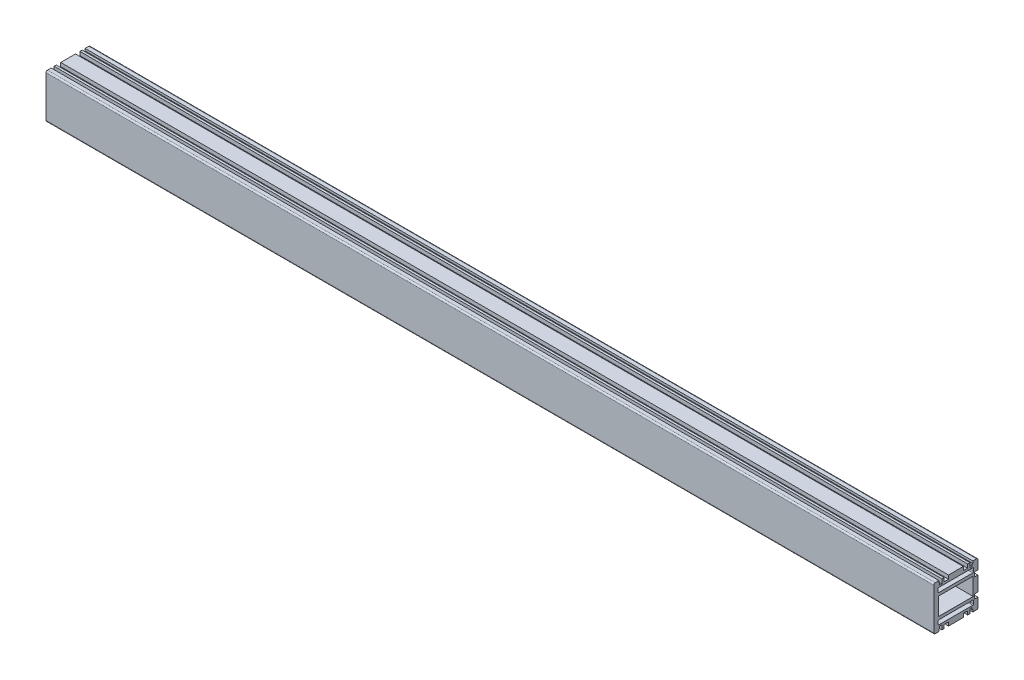
SolidWorks part; units mm, degrees
ref_plane "前视基准面" through (0, 0, 0) normal (0, 0, 1) x (1, 0, 0)
ref_plane "上视基准面" through (0, 0, 0) normal (0, 1, 0) x (1, 0, 0)
ref_plane "右视基准面" through (0, 0, 0) normal (1, 0, 0) x (0, 0, -1)
sketch "草图1" plane through (0, 0, 0) normal (1, 0, 0) x (0, 0, -1)
  line L0 (-15, 15) -> (15, -15) construction
  line L1 (-14, 15) -> (-11.5, 15)
  line L2 (-15, 14) -> (-15, -14)
  line L3 (-14, -15) -> (-11.5, -15)
  line L4 (15, 14) -> (15, 8)
  line L5 (15, 15) -> (-15, -15) construction
  line L6 (-11.5, 15) -> (-11.5, 13.5)
  line L7 (-11.5, 13.5) -> (-11.4, 13.5)
  line L8 (-11, 13.1) -> (-11, 12)
  line L9 (-11, 12) -> (-9.5, 12)
  line L10 (-9.5, 12) -> (-9.5, 15)
  line L11 (-9.5, 15) -> (-8, 15)
  line L12 (-8, 15) -> (-8, 12.5)
  line L13 (-8, 12.5) -> (-5, 12.5)
  line L14 (-5, 12.5) -> (-5, 15)
  line L15 (-5, 15) -> (5, 15)
  line L16 (0, 21.5201) -> (0, -18.309) construction
  line L17 (0, 55) -> (0, -55) construction
  line L18 (5, 12.5) -> (5, 15)
  line L19 (8, 12.5) -> (5, 12.5)
  line L20 (8, 15) -> (8, 12.5)
  line L21 (9.5, 15) -> (8, 15)
  line L22 (9.5, 12) -> (9.5, 15)
  line L23 (11, 12) -> (9.5, 12)
  line L24 (11, 13.1) -> (11, 12)
  line L25 (11.5, 13.5) -> (11.4, 13.5)
  line L26 (11.5, 15) -> (11.5, 13.5)
  line L27 (8, 15) -> (9.5, 15)
  line L28 (11.5, 15) -> (14, 15)
  line L29 (-19.8303, 0) -> (22.13, 0) construction
  line L30 (55, 0) -> (-55, 0) construction
  line L31 (8, -15) -> (9.5, -15)
  line L32 (11.5, -15) -> (11.5, -13.5)
  line L33 (11.5, -13.5) -> (11.4, -13.5)
  line L34 (11, -13.1) -> (11, -12)
  line L35 (11, -12) -> (9.5, -12)
  line L36 (9.5, -12) -> (9.5, -15)
  line L37 (9.5, -15) -> (8, -15)
  line L38 (8, -15) -> (8, -12.5)
  line L39 (8, -12.5) -> (5, -12.5)
  line L40 (5, -12.5) -> (5, -15)
  line L41 (-5, -15) -> (5, -15)
  line L42 (-5, -12.5) -> (-5, -15)
  line L43 (-8, -12.5) -> (-5, -12.5)
  line L44 (-8, -15) -> (-8, -12.5)
  line L45 (-9.5, -15) -> (-8, -15)
  line L46 (-9.5, -12) -> (-9.5, -15)
  line L47 (-11, -12) -> (-9.5, -12)
  line L48 (-11, -13.1) -> (-11, -12)
  line L49 (-11.5, -13.5) -> (-11.4, -13.5)
  line L50 (-11.5, -15) -> (-11.5, -13.5)
  line L51 (-9.5, -15) -> (-8, -15)
  line L52 (-5, -15) -> (5, -15)
  line L53 (8, -15) -> (9.5, -15)
  line L54 (11.5, -15) -> (14, -15)
  line L55 (15, 8) -> (12.5, 8)
  line L56 (12.5, 8) -> (12.5, 5)
  line L57 (12.5, 5) -> (15, 5)
  line L58 (12.5, -5) -> (15, -5)
  line L59 (12.5, -8) -> (12.5, -5)
  line L60 (15, -8) -> (12.5, -8)
  line L61 (15, 5) -> (15, -5)
  line L62 (15, -8) -> (15, -14)
  line L63 (12, -10.5) -> (12, -8.5)
  line L64 (-11.5, 11) -> (11.5, 11)
  line L65 (-12, 10.5) -> (-12, 8.5)
  line L66 (-11.5, 8) -> (11.5, 8)
  line L67 (12, 10.5) -> (12, 8.5)
  line L68 (-11.5, -8) -> (11.5, -8)
  line L69 (-12, -10.5) -> (-12, -8.5)
  line L70 (-11.5, -11) -> (11.5, -11)
  line L72 (-11.75, 6) -> (11.75, 6)
  line L73 (-11.75, 6) -> (-11.75, -6)
  line L74 (-11.75, -6) -> (11.75, -6)
  line L75 (11.75, 6) -> (11.75, -6)
  arc A0 (12, 8.5) -> (11.5, 8) centre (11.5, 8.5) cw
  arc A1 (11.5, 11) -> (12, 10.5) centre (11.5, 10.5) cw
  arc A2 (-11.5, 11) -> (-12, 10.5) centre (-11.5, 10.5) ccw
  arc A3 (-11.5, 8) -> (-12, 8.5) centre (-11.5, 8.5) cw
  arc A4 (-11, -13.1) -> (-11.4, -13.5) centre (-11.4, -13.1) cw
  arc A5 (11.4, -13.5) -> (11, -13.1) centre (11.4, -13.1) cw
  arc A6 (11.4, 13.5) -> (11, 13.1) centre (11.4, 13.1) ccw
  arc A7 (-11, 13.1) -> (-11.4, 13.5) centre (-11.4, 13.1) ccw
  arc A8 (-11.5, -8) -> (-12, -8.5) centre (-11.5, -8.5) ccw
  arc A9 (-11.5, -11) -> (-12, -10.5) centre (-11.5, -10.5) cw
  arc A10 (11.5, -11) -> (12, -10.5) centre (11.5, -10.5) ccw
  arc A11 (12, -8.5) -> (11.5, -8) centre (11.5, -8.5) ccw
  arc A12 (14, 15) -> (15, 14) centre (14, 14) cw
  arc A13 (14, -15) -> (15, -14) centre (14, -14) ccw
  arc A14 (-15, -14) -> (-14, -15) centre (-14, -14) ccw
  arc A15 (-15, 14) -> (-14, 15) centre (-14, 14) cw
  point P69 (12, 11)
  point P72 (-12, 11)
  point P77 (-11, -13.5)
  point P80 (11, -13.5)
  point P83 (11, 13.5)
  point P86 (-11, 13.5)
  point P99 (-12, -11)
  point P100 (12, -11)
  dimension "D17" = 0.5
  dimension "D18" = 0.4
  dimension "D21" = 1
  dimension "D1" = 3.5
  dimension "D2" = 1.5
  dimension "D3" = 0.5
  dimension "D4" = 1.5
  dimension "D5" = 3
  dimension "D6" = 30
  dimension "D7" = 30
  dimension "D8" = 1.5
  dimension "D9" = 2.5
  dimension "D10" = 3
  dimension "D11" = 2.5
  dimension "D12" = 7
  dimension "D13" = 3
  dimension "D14" = 4
  dimension "D15" = 3
  dimension "D16" = 24
  dimension "D19" = 23.5
  dimension "D20" = 12
extrude "凸台-拉伸1" add sketch "草图1" along normal mid plane 602 contours A15 L2 A14 L3 L50 L49 A4 L48 L47 L46 L45 L44 L43 L42 L41 L40 L39 L38 L31 L36 L35 L34 A5 L33 L32 L54 A13 L62 L60 L59 L58 L61 L57 L56 L55 L4 A12 L28 L26 L25 A6 L24 L23 L22 L21 L20 L19 L18 L15 L14 L13
hole_wizard "M6 螺纹孔1" positions "草图3" profile "草图2" tap size "M6" standard "GB"
sketch "草图3" plane through (0, -15, 0) normal (0, -1, 0) x (1, 0, 0)
  line L0 (301, 5) -> (301, -5) construction
  line L1 (301, -15) -> (-301, -15) construction
  point P0 (281, 0)
  point P1 (266, 0)
  point P4 (-281, 0)
  point P7 (-266, 0)
  dimension "D1" = 20
  dimension "D2" = 15
sketch "草图2" plane through (281, -15, 0) normal (1, 0, 0) x (0, 0, -1)
  line L0 (0, 0) -> (0, 16.5022)
  line L1 (0, 16.5022) -> (2.5, 15)
  line L2 (2.5, 15) -> (2.5, 0)
  line L5 (2.5, 0) -> (0, 0)
  line L10 (0, 16.5022) -> (-2.5, 15) construction
  line L11 (0, -6.35) -> (0, 107.95) construction
  dimension "螺纹孔钻头直径" = 5
  dimension "螺纹孔钻头深度" = 15
  dimension "导头角度" = 118
cosmetic thread "孔螺蚊线1" parameters "D1"=9, "D2"=6
cosmetic thread "孔螺蚊线2" parameters "D1"=9, "D2"=6
cosmetic thread "孔螺蚊线11" parameters "D1"=9, "D2"=6
cosmetic thread "孔螺蚊线12" parameters "D1"=9, "D2"=6
hole_wizard "M6 螺纹孔2" positions "草图5" profile "草图4" tap size "M6" standard "GB"
sketch "草图5" plane through (0, 0, -15) normal (0, 0, -1) x (-1, 0, 0)
  line L0 (-301, 5) -> (-301, -5) construction
  line L1 (-301, -15) -> (301, -15) construction
  point P0 (-281, 0)
  point P1 (-266, 0)
  point P4 (14, 0)
  point P7 (29, 0)
  point P10 (99, 0)
  point P13 (114, 0)
  dimension "D1" = 20
  dimension "D2" = 15
sketch "草图4" plane through (281, 0, -15) normal (1, 0, 0) x (0, 1, 0)
  line L0 (0, 0) -> (0, 16.5022)
  line L1 (0, 16.5022) -> (2.5, 15)
  line L2 (2.5, 15) -> (2.5, 0)
  line L5 (2.5, 0) -> (0, 0)
  line L10 (0, 16.5022) -> (-2.5, 15) construction
  line L11 (0, -6.35) -> (0, 107.95) construction
  dimension "螺纹孔钻头直径" = 5
  dimension "螺纹孔钻头深度" = 15
  dimension "导头角度" = 118
cosmetic thread "孔螺蚊线5" parameters "D1"=3.25, "D2"=6
cosmetic thread "孔螺蚊线6" parameters "D1"=3.25, "D2"=6
cosmetic thread "孔螺蚊线7" parameters "D1"=3.25, "D2"=6
cosmetic thread "孔螺蚊线8" parameters "D1"=3.25, "D2"=6
cosmetic thread "孔螺蚊线9" parameters "D1"=3.25, "D2"=6
cosmetic thread "孔螺蚊线10" parameters "D1"=3.25, "D2"=6
hole_wizard "M4 螺纹孔1" positions "草图7" profile "草图6" tap size "M4" standard "GB"
sketch "草图7" plane through (0, 0, -15) normal (0, 0, -1) x (-1, 0, 0)
  line L0 (-301, 15) -> (301, 15) construction
  line L1 (-301, 14) -> (-301, 8) construction
  point P0 (-226, 0)
  point P1 (-126, 0)
  point P3 (-26, 0)
  dimension "D1" = 15
  dimension "D2" = 75
  dimension "D3" = 100
  dimension "D4" = 100
sketch "草图6" plane through (226, 0, -15) normal (1, 0, 0) x (0, 1, 0)
  line L0 (0, 0) -> (0, 11.0914)
  line L1 (0, 11.0914) -> (1.65, 10.1)
  line L2 (1.65, 10.1) -> (1.65, 0)
  line L5 (1.65, 0) -> (0, 0)
  line L10 (0, 11.0914) -> (-1.65, 10.1) construction
  line L11 (0, -6.35) -> (0, 107.95) construction
  dimension "螺纹孔钻头直径" = 3.3
  dimension "螺纹孔钻头深度" = 10.1
  dimension "导头角度" = 118
cosmetic thread "孔螺蚊线13" parameters "D1"=3.25, "D2"=4
cosmetic thread "孔螺蚊线14" parameters "D1"=3.25, "D2"=4
cosmetic thread "孔螺蚊线15" parameters "D1"=3.25, "D2"=4
